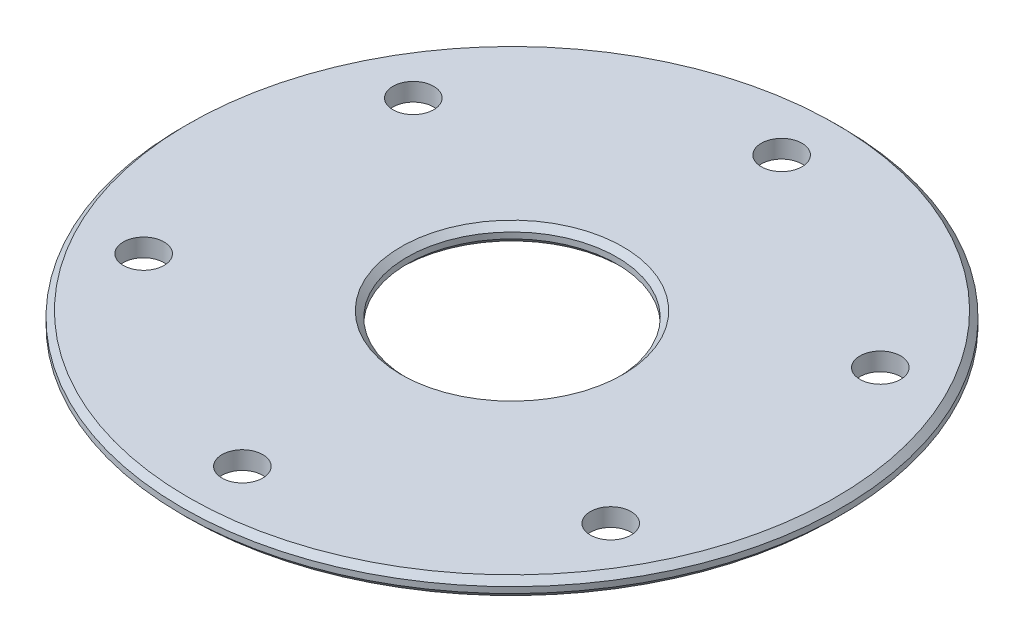
SolidWorks part; units mm, degrees
ref_plane "前视基准面" through (0, 0, 0) normal (0, 0, 1) x (1, 0, 0)
ref_plane "上视基准面" through (0, 0, 0) normal (0, 1, 0) x (1, 0, 0)
ref_plane "右视基准面" through (0, 0, 0) normal (1, 0, 0) x (0, 0, -1)
sketch "草图1" plane through (0, 0, 0) normal (0, 1, 0) x (1, 0, 0)
  circle A0 centre (0, 0) radius 55
  dimension "D1" = 110
extrude "凸台-拉伸1" add sketch "草图1" along normal blind 3
sketch "草图2" plane through (0, 3, 0) normal (0, 1, 0) x (1, 0, 0)
  line L0 (0, 0) -> (0, 62.1923)
  circle A0 centre (0, 0) radius 17.5
  circle A1 centre (0, 0) radius 45
  dimension "D1" = 35
  dimension "D2" = 90
hole_wizard "M8 螺纹孔的螺纹孔钻头1" positions "草图3" profile "草图4" hole size "M8" standard "GB"
sketch "草图3" plane through (0, 3, 0) normal (0, 1, 0) x (1, 0, 0)
  line L0 (0, 0) -> (0, 62.1923) construction
  circle A0 centre (0, 0) radius 45 construction
  point P0 (0, 45)
sketch "草图4" plane through (0, 3, -45) normal (1, 0, 0) x (0, 0, 1)
  line L0 (0, 0) -> (0, 18.0429)
  line L1 (0, 18.0429) -> (3.4, 16)
  line L2 (3.4, 16) -> (3.4, 0)
  line L5 (3.4, 0) -> (0, 0)
  line L10 (0, 18.0429) -> (-3.4, 16) construction
  line L11 (0, -6.35) -> (0, 107.95) construction
  dimension "孔直径" = 6.8
  dimension "孔深度" = 16
  dimension "导头角度" = 118
pattern_circular "阵列(圆周)1" count 6 over 360 about axis through (0, 0, 0) along (0, 1, 0) of "M8 螺纹孔的螺纹孔钻头1"
extrude "切除-拉伸1" cut sketch "草图2" against normal blind 3
chamfer "倒角1" distance 1 angle 45 2 edges at (0, 3, 55) (0, 0, 55)
chamfer "倒角2" distance 1 angle 45 2 edges at (0, 3, 17.5) (0, 0, 17.5)
